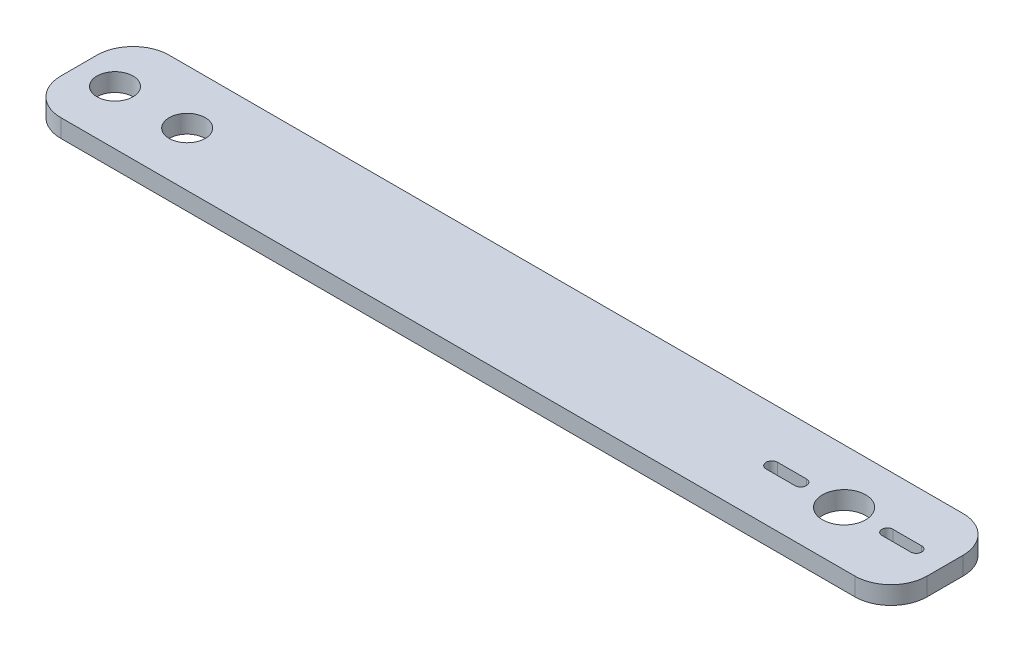
SolidWorks part; units mm, degrees
material "Thornel Mat VMA"
ref_plane "Front Plane" through (0, 0, 0) normal (0, 0, 1) x (1, 0, 0)
ref_plane "Top Plane" through (0, 0, 0) normal (0, 1, 0) x (1, 0, 0)
ref_plane "Right Plane" through (0, 0, 0) normal (1, 0, 0) x (0, 0, -1)
sketch "Sketch1" plane through (0, 0, 0) normal (0, 1, 0) x (1, 0, 0)
  line L1 (-54.398, 16.9499) -> (98.002, 16.9499)
  line L2 (-54.398, 16.9499) -> (-54.398, -2.1001)
  line L3 (-54.398, -2.1001) -> (98.002, -2.1001)
  line L4 (98.002, 16.9499) -> (98.002, -2.1001)
  dimension "D1" = 152.4
  dimension "D2" = 19.05
extrude "Boss-Extrude1" add sketch "Sketch1" along normal blind 3.175
fillet "Fillet1" radius 6.35 4 edges at (98.002, 1.5875, -16.9499) (98.002, 1.5875, 2.1001) (-54.398, 1.5875, -16.9499) (-54.398, 1.5875, 2.1001)
sketch "Sketch2" plane through (0, 3.175, 0) normal (0, 1, 0) x (1, 0, 0)
  line L0 (-54.398, 7.4249) -> (-1.9555, 7.4249) construction
  line L1 (-54.398, 10.5999) -> (-54.398, 4.2499) construction
  line L2 (87.842, 7.4249) -> (92.922, 7.4249) construction
  line L3 (87.842, 8.3774) -> (92.922, 8.3774)
  line L4 (87.842, 6.4724) -> (92.922, 6.4724)
  line L5 (72.602, 7.4249) -> (67.522, 7.4249) construction
  line L6 (72.602, 6.4089) -> (67.522, 6.4089)
  line L7 (72.602, 8.4409) -> (67.522, 8.4409)
  line L8 (98.002, 4.2499) -> (98.002, 10.5999) construction
  line L9 (98.002, 7.4249) -> (30.5784, 7.4249) construction
  circle A0 centre (-48.048, 7.4249) radius 3.175
  circle A1 centre (-35.348, 7.4249) radius 3.175
  circle A2 centre (80.222, 7.4249) radius 3.81
  arc A3 (87.842, 8.3774) -> (87.842, 6.4724) centre (87.842, 7.4249) ccw
  arc A4 (92.922, 6.4724) -> (92.922, 8.3774) centre (92.922, 7.4249) ccw
  arc A5 (72.602, 6.4089) -> (72.602, 8.4409) centre (72.602, 7.4249) ccw
  arc A6 (67.522, 8.4409) -> (67.522, 6.4089) centre (67.522, 7.4249) ccw
  point P12 (90.382, 7.4249)
  point P17 (70.062, 7.4249)
  dimension "D1" = 6.35
  dimension "D2" = 6.35
  dimension "D5" = 7.62
  dimension "D10" = 1.905
  dimension "D3" = 6.35
  dimension "D4" = 12.7
  dimension "D6" = 5.08
  dimension "D7" = 5.08
  dimension "D8" = 7.62
  dimension "D9" = 7.62
  dimension "D11" = 2.032
  dimension "D12" = 5.08
extrude "Cut-Extrude1" cut sketch "Sketch2" against normal through all
